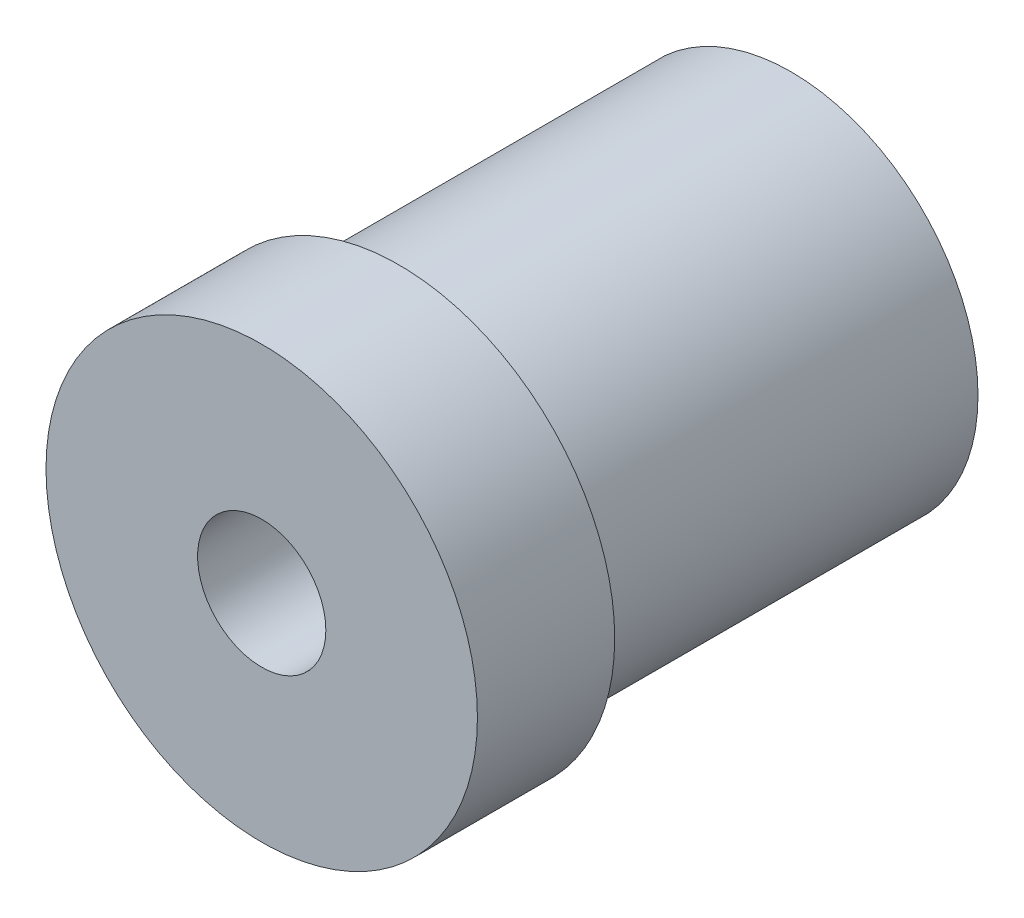
SolidWorks part; units mm, degrees
ref_plane "Front Plane" through (0, 0, 0) normal (0, 0, 1) x (1, 0, 0)
ref_plane "Top Plane" through (0, 0, 0) normal (0, 1, 0) x (1, 0, 0)
ref_plane "Right Plane" through (0, 0, 0) normal (1, 0, 0) x (0, 0, -1)
sketch "Sketch1" plane through (0, 0, 0) normal (0, 0, 1) x (1, 0, 0)
  circle A0 centre (0, 0) radius 9.525
  circle A1 centre (0, 0) radius 3.25
  dimension "D1" = 6.5
  dimension "D2" = 19.05
extrude "Boss-Extrude1" add sketch "Sketch1" along normal blind 20
sketch "Sketch2" plane through (0, 0, 20) normal (0, 0, 1) x (1, 0, 0)
  circle A0 centre (0, 0) radius 3.27
  circle A1 centre (0, 0) radius 11
extrude "Boss-Extrude2" add sketch "Sketch2" along normal blind 7 contours A1
sketch "Sketch3" plane through (0, 0, 27) normal (0, 0, 1) x (1, 0, 0)
  circle A0 centre (0, 0) radius 3.27
extrude "Cut-Extrude1" cut sketch "Sketch3" against normal blind 7
